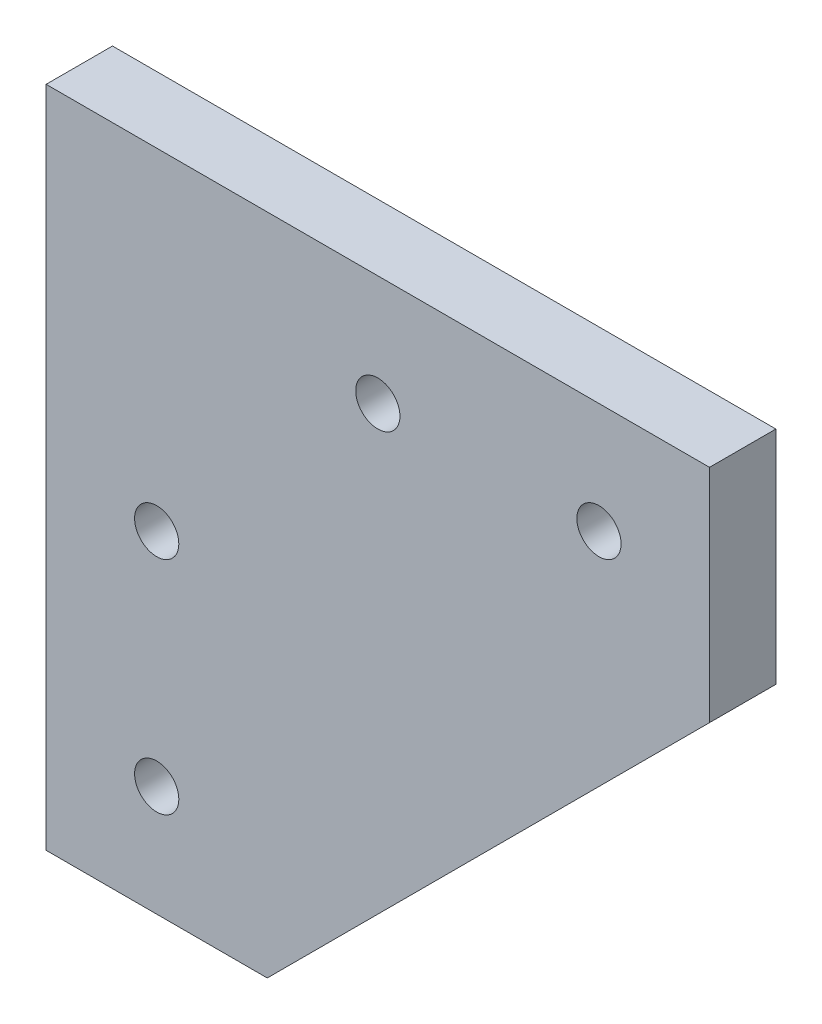
SolidWorks part; units mm, degrees
ref_plane "Front Plane" through (0, 0, 0) normal (0, 0, 1) x (1, 0, 0)
ref_plane "Top Plane" through (0, 0, 0) normal (0, 1, 0) x (1, 0, 0)
ref_plane "Right Plane" through (0, 0, 0) normal (1, 0, 0) x (0, 0, -1)
sketch "Sketch1" plane through (0, 0, 0) normal (0, 0, 1) x (1, 0, 0)
  line L0 (20, -60) -> (60, -20)
  line L1 (0, 0) -> (60, 0)
  line L2 (0, 0) -> (0, -60) construction
  line L3 (0, -60) -> (20, -60)
  line L4 (60, 0) -> (60, -20)
  line L5 (10, -60) -> (10, -50) construction
  line L6 (10, -50) -> (10, -30) construction
  line L7 (10, -30) -> (10, -10) construction
  line L8 (10, -10) -> (30, -10) construction
  line L9 (30, -10) -> (50, -10) construction
  line L10 (50, -10) -> (60, -10) construction
  line L11 (0, 0) -> (0, -60)
  line L12 (-45, -60) -> (0, -60) construction
  line L13 (-45, -60) -> (-45, 0) construction
  line L14 (-45, 0) -> (0, 0) construction
  line L15 (0, -60) -> (0, 0) construction
  circle A0 centre (50, -10) radius 2
  circle A1 centre (30, -10) radius 2
  circle A2 centre (10, -50) radius 2
  circle A3 centre (10, -30) radius 2
  dimension "D3" = 4
  dimension "D1" = 60
  dimension "D2" = 20
  dimension "D4" = 10
  dimension "D5" = 30
  dimension "D6" = 30
  dimension "D7" = 10
  dimension "D8" = 45
  dimension "D9" = 60
extrude "Boss-Extrude1" add sketch "Sketch1" along normal blind 6
